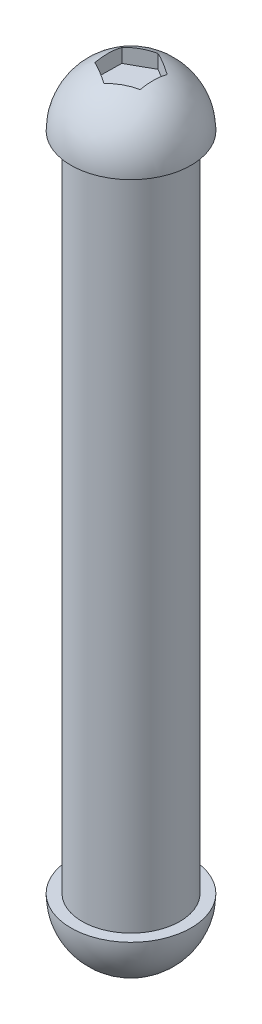
SolidWorks part; units mm, degrees
ref_plane "前视基准面" through (0, 0, 0) normal (0, 0, 1) x (1, 0, 0)
ref_plane "上视基准面" through (0, 0, 0) normal (0, 1, 0) x (1, 0, 0)
ref_plane "右视基准面" through (0, 0, 0) normal (1, 0, 0) x (0, 0, -1)
other "Configuration Table"
sketch "草图1" plane through (0, 0, 0) normal (0, 1, 0) x (1, 0, 0)
  line L0 (0.2272, 2.9914) -> (-0.2272, -2.9914) construction
  circle A0 centre (0, 0) radius 3
revolve "旋转1" add sketch "草图1" angle 180 about L0
ref_plane "基准面1" through (0, -3, 0) normal (0, -1, 0) x (-1, 0, 0)
sketch "草图2" plane through (0, -3, 0) normal (0, -1, 0) x (-1, 0, 0)
  line L1 (1.1614, -0.6466) -> (1.1406, 0.6825)
  line L2 (1.1406, 0.6825) -> (-0.0207, 1.3291)
  line L3 (-0.0207, 1.3291) -> (-1.1614, 0.6466)
  line L4 (-1.1614, 0.6466) -> (-1.1406, -0.6825)
  line L5 (-1.1406, -0.6825) -> (0.0207, -1.3291)
  line L6 (0.0207, -1.3291) -> (1.1614, -0.6466)
  circle A0 centre (0, 0) radius 1.1511 construction
extrude "切除-拉伸1" cut sketch "草图2" against normal blind 1
sketch "草图3" plane through (0, 0, 0) normal (0, 1, 0) x (1, 0, 0)
  circle A0 centre (0, 0) radius 2.44
extrude "凸台-拉伸1" add sketch "草图3" along normal blind 16.5
mirror "镜向1" about plane through (0, 16.5, 0) normal (0, 1, 0) of bodies 108
